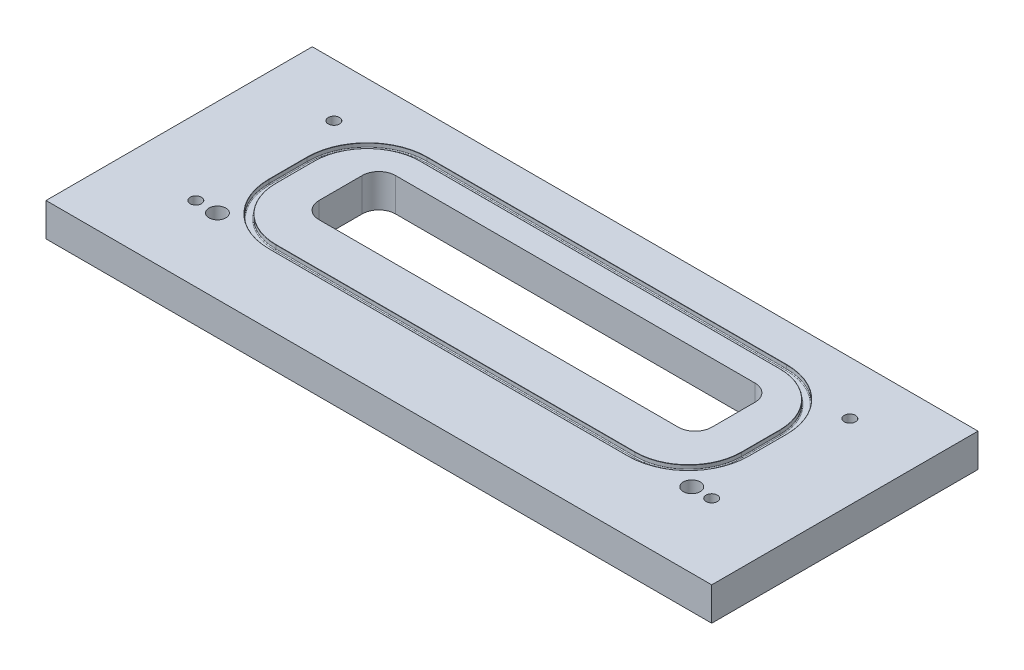
SolidWorks part; units mm, degrees
ref_plane "정면" through (0, 0, 0) normal (0, 0, 1) x (1, 0, 0)
ref_plane "윗면" through (0, 0, 0) normal (0, 1, 0) x (1, 0, 0)
ref_plane "우측면" through (0, 0, 0) normal (1, 0, 0) x (0, 0, -1)
sketch "스케치1" plane through (0, 0, 0) normal (0, 1, 0) x (1, 0, 0)
  line L1 (0, 0) -> (400, 0)
  line L2 (0, 0) -> (0, 160)
  line L3 (0, 160) -> (400, 160)
  line L4 (400, 0) -> (400, 160)
  dimension "D1" = 400
  dimension "D2" = 160
extrude "보스-돌출1" add sketch "스케치1" along normal mid plane 20
sketch "스케치2" plane through (0, 10, 0) normal (0, 1, 0) x (1, 0, 0)
  line L0 (0, 0) -> (400, 0) construction
  line L1 (92, 135) -> (308, 135) construction
  line L2 (58, 101) -> (58, 78) construction
  line L3 (92, 44) -> (308, 44) construction
  line L4 (342, 101) -> (342, 78) construction
  line L5 (0, 160) -> (0, 0) construction
  line L6 (92, 137.05) -> (308, 137.05)
  line L7 (344.05, 101) -> (344.05, 78)
  line L8 (92, 41.95) -> (308, 41.95)
  line L9 (55.95, 101) -> (55.95, 78)
  line L10 (92, 132.95) -> (308, 132.95)
  line L11 (339.95, 101) -> (339.95, 78)
  line L12 (92, 46.05) -> (308, 46.05)
  line L13 (60.05, 101) -> (60.05, 78)
  arc A0 (58, 78) -> (92, 44) centre (92, 78) ccw construction
  arc A1 (308, 44) -> (342, 78) centre (308, 78) ccw construction
  arc A2 (308, 135) -> (342, 101) centre (308, 101) cw construction
  arc A3 (92, 135) -> (58, 101) centre (92, 101) ccw construction
  arc A4 (308, 137.05) -> (344.05, 101) centre (308, 101) cw
  arc A5 (308, 41.95) -> (344.05, 78) centre (308, 78) ccw
  arc A6 (55.95, 78) -> (92, 41.95) centre (92, 78) ccw
  arc A7 (92, 137.05) -> (55.95, 101) centre (92, 101) ccw
  arc A8 (308, 132.95) -> (339.95, 101) centre (308, 101) cw
  arc A9 (308, 46.05) -> (339.95, 78) centre (308, 78) ccw
  arc A10 (60.05, 78) -> (92, 46.05) centre (92, 78) ccw
  arc A11 (92, 132.95) -> (60.05, 101) centre (92, 101) ccw
  dimension "D5" = 34
  dimension "D1" = 44
  dimension "D2" = 91
  dimension "D3" = 284
  dimension "D4" = 58
  dimension "D6" = 2.05
  dimension "D7" = 2.05
extrude "컷-돌출1" cut sketch "스케치2" against normal blind 2.7
fillet "필렛1" radius 0.13 16 edges at (200, 10, -132.95) (330.5921, 10, -123.5921) (339.95, 10, -89.5) (330.5921, 10, -55.4079) (200, 10, -46.05) (69.4079, 10, -55.4079) (60.05, 10, -89.5) (200, 10, -137.05) (333.4912, 10, -126.4912) (344.05, 10, -89.5) (333.4912, 10, -52.5088) (200, 10, -41.95) (66.5088, 10, -52.5088) (55.95, 10, -89.5) (69.4079, 10, -123.5921) (66.5088, 10, -126.4912)
fillet "필렛2" radius 0.5 16 edges at (69.4079, 7.3, -123.5921) (200, 7.3, -132.95) (330.5921, 7.3, -123.5921) (339.95, 7.3, -89.5) (330.5921, 7.3, -55.4079) (200, 7.3, -46.05) (69.4079, 7.3, -55.4079) (200, 7.3, -137.05) (333.4912, 7.3, -126.4912) (344.05, 7.3, -89.5) (333.4912, 7.3, -52.5088) (200, 7.3, -41.95) (66.5088, 7.3, -52.5088) (55.95, 7.3, -89.5) (60.05, 7.3, -89.5) (66.5088, 7.3, -126.4912)
sketch "스케치3" plane through (0, 10, 0) normal (0, 1, 0) x (1, 0, 0)
  line L0 (0, 0) -> (400, 0) construction
  line L1 (92, 118) -> (308, 118)
  line L2 (82, 108) -> (82, 82)
  line L3 (92, 72) -> (308, 72)
  line L4 (318, 108) -> (318, 82)
  line L6 (0, 160) -> (0, 0) construction
  line L7 (400, 0) -> (400, 160) construction
  arc A5 (92, 118) -> (82, 108) centre (92, 108) ccw
  arc A6 (308, 118) -> (318, 108) centre (308, 108) cw
  arc A7 (308, 72) -> (318, 82) centre (308, 82) ccw
  arc A8 (82, 82) -> (92, 72) centre (92, 82) ccw
  point P14 (318, 118)
  point P18 (318, 72)
  dimension "D5" = 10
  dimension "D1" = 72
  dimension "D2" = 46
  dimension "D3" = 82
  dimension "D4" = 82
extrude "컷-돌출2" cut sketch "스케치3" against normal through all
sketch "스케치4" plane through (0, 10, 0) normal (0, 1, 0) x (1, 0, 0)
  line L2 (0, 0) -> (400, 0) construction
  point P9 (343, 45)
  point P10 (58, 45)
  dimension "D1" = 58
  dimension "D2" = 45
  dimension "D3" = 285
sketch "스케치7" plane through (0, 10, 0) normal (0, 1, 0) x (1, 0, 0)
  point P0 (58, 45)
  point P3 (343, 45)
hole_wizard "M12 나사 구멍1" positions "스케치7" profile "스케치6" tap size "M12" standard "ISO"
sketch "스케치6" plane through (58, 10, -45) normal (1, 0, 0) x (0, 0, 1)
  line L0 (0, 0) -> (0, 18.0644)
  line L1 (0, 18.0644) -> (5.1, 15)
  line L2 (5.1, 15) -> (5.1, 0)
  line L5 (5.1, 0) -> (0, 0)
  line L10 (0, 18.0644) -> (-5.1, 15) construction
  line L11 (0, -6.35) -> (0, 107.95) construction
  dimension "탭 드릴 지름" = 10.2
  dimension "탭 드릴 깊이" = 15
  dimension "드릴 각도" = 118
cosmetic thread "구멍 나사산1" parameters "D1"=10, "D2"=12
cosmetic thread "구멍 나사산2" parameters "D1"=10, "D2"=12
sketch "스케치8" plane through (0, 10, 0) normal (0, 1, 0) x (1, 0, 0)
  line L0 (0, 0) -> (400, 0) construction
  point P0 (45, 128)
  point P1 (45, 45)
  point P2 (355, 128)
  point P3 (355, 45)
  dimension "D1" = 45
  dimension "D2" = 45
  dimension "D3" = 83
  dimension "D4" = 310
hole_wizard "M8 나사 구멍1" positions "스케치8" profile "스케치9" tap size "M8" standard "ISO"
sketch "스케치9" plane through (45, 10, -128) normal (1, 0, 0) x (0, 0, 1)
  line L0 (0, 0) -> (0, 17.0429)
  line L1 (0, 17.0429) -> (3.4, 15)
  line L2 (3.4, 15) -> (3.4, 0)
  line L5 (3.4, 0) -> (0, 0)
  line L10 (0, 17.0429) -> (-3.4, 15) construction
  line L11 (0, -6.35) -> (0, 107.95) construction
  dimension "탭 드릴 지름" = 6.8
  dimension "탭 드릴 깊이" = 15
  dimension "드릴 각도" = 118
cosmetic thread "구멍 나사산3" parameters "D1"=10, "D2"=8
cosmetic thread "구멍 나사산4" parameters "D1"=10, "D2"=8
cosmetic thread "구멍 나사산5" parameters "D1"=10, "D2"=8
cosmetic thread "구멍 나사산6" parameters "D1"=10, "D2"=8
